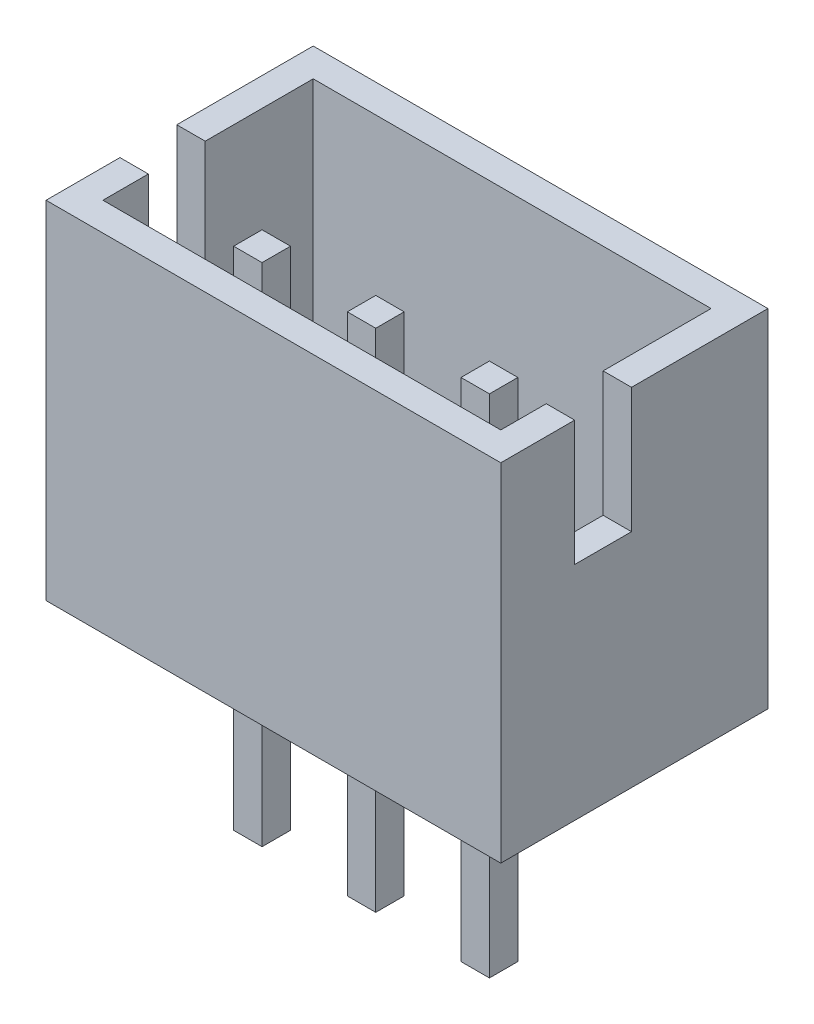
SolidWorks part; units mm, degrees
ref_plane "Front Plane" through (0, 0, 0) normal (0, 0, 1) x (1, 0, 0)
ref_plane "Top Plane" through (0, 0, 0) normal (0, 1, 0) x (1, 0, 0)
ref_plane "Right Plane" through (0, 0, 0) normal (1, 0, 0) x (0, 0, -1)
sketch "Sketch1" plane through (0, 0, 0) normal (0, 1, 0) x (1, 0, 0)
  line L1 (4, -2.35) -> (-4, -2.35)
  line L2 (4, -2.35) -> (4, 2.35)
  line L3 (4, 2.35) -> (-4, 2.35)
  line L4 (-4, -2.35) -> (-4, 2.35)
  line L5 (4, -2.35) -> (-4, 2.35) construction
  line L6 (4, 2.35) -> (-4, -2.35) construction
  point P0 (0, 0)
  dimension "D1" = 4.7
  dimension "D2" = 8
extrude "Boss-Extrude1" add sketch "Sketch1" along normal blind 6.1
shell "Shell1" thickness 0.5
sketch "Sketch2" plane through (0, 0.5, 0) normal (0, 1, 0) x (1, 0, 0)
  line L0 (-3.5, -0.55) -> (3.5, -0.55) construction
  line L1 (-3.5, 1.85) -> (-3.5, -1.85) construction
  line L2 (3.5, -1.85) -> (3.5, 1.85) construction
  line L3 (-4, -2.35) -> (4, -2.35) construction
  line L4 (0.25, -0.8) -> (0.25, -0.3)
  line L5 (-1.75, -0.8) -> (-2.25, -0.8)
  line L6 (-1.75, -0.8) -> (-1.75, -0.3)
  line L7 (-1.75, -0.3) -> (-2.25, -0.3)
  line L8 (-2.25, -0.8) -> (-2.25, -0.3)
  line L9 (-1.75, -0.8) -> (-2.25, -0.3) construction
  line L10 (-1.75, -0.3) -> (-2.25, -0.8) construction
  line L11 (0.25, -0.8) -> (-0.25, -0.8)
  line L12 (-0.25, -0.8) -> (-0.25, -0.3)
  line L13 (0.25, -0.3) -> (-0.25, -0.3)
  line L14 (2.25, -0.8) -> (2.25, -0.3)
  line L15 (2.25, -0.8) -> (1.75, -0.8)
  line L16 (1.75, -0.8) -> (1.75, -0.3)
  line L17 (2.25, -0.3) -> (1.75, -0.3)
  line L18 (-1.75, -0.8) -> (0.25, -0.8) construction
  point P8 (-2, -0.55)
  point P13 (0, -0.3)
  dimension "D1" = 1.8
  dimension "D2" = 0.5
  dimension "D4" = 2
  dimension "D3" = 3
extrude "Boss-Extrude2" add sketch "Sketch2" along normal blind 5 and the other way blind 3.9 separate body
sketch "Sketch3" plane through (-4, 0, 0) normal (-1, 0, 0) x (0, 0, 1)
  line L0 (-2.35, 6.1) -> (2.35, 6.1) construction
  line L1 (1.05, 3.9) -> (0.05, 3.9)
  line L2 (1.05, 3.9) -> (1.05, 6.1)
  line L3 (1.05, 6.1) -> (0.05, 6.1)
  line L4 (0.05, 3.9) -> (0.05, 6.1)
  line L5 (1.05, 3.9) -> (0.05, 6.1) construction
  line L6 (1.05, 6.1) -> (0.05, 3.9) construction
  line L7 (-2.35, 0) -> (2.35, 0) construction
  line L8 (0.3, -3.4) -> (0.8, -3.4) construction
  point P0 (0.55, 5)
  point P12 (0.55, -3.4)
  dimension "D1" = 5
  dimension "D2" = 1
extrude "Cut-Extrude1" cut sketch "Sketch3" against normal up to surface (7.5 mm away)
mirror "Mirror1" about plane through (0, 0, 0) normal (1, 0, 0) of "Cut-Extrude1"
